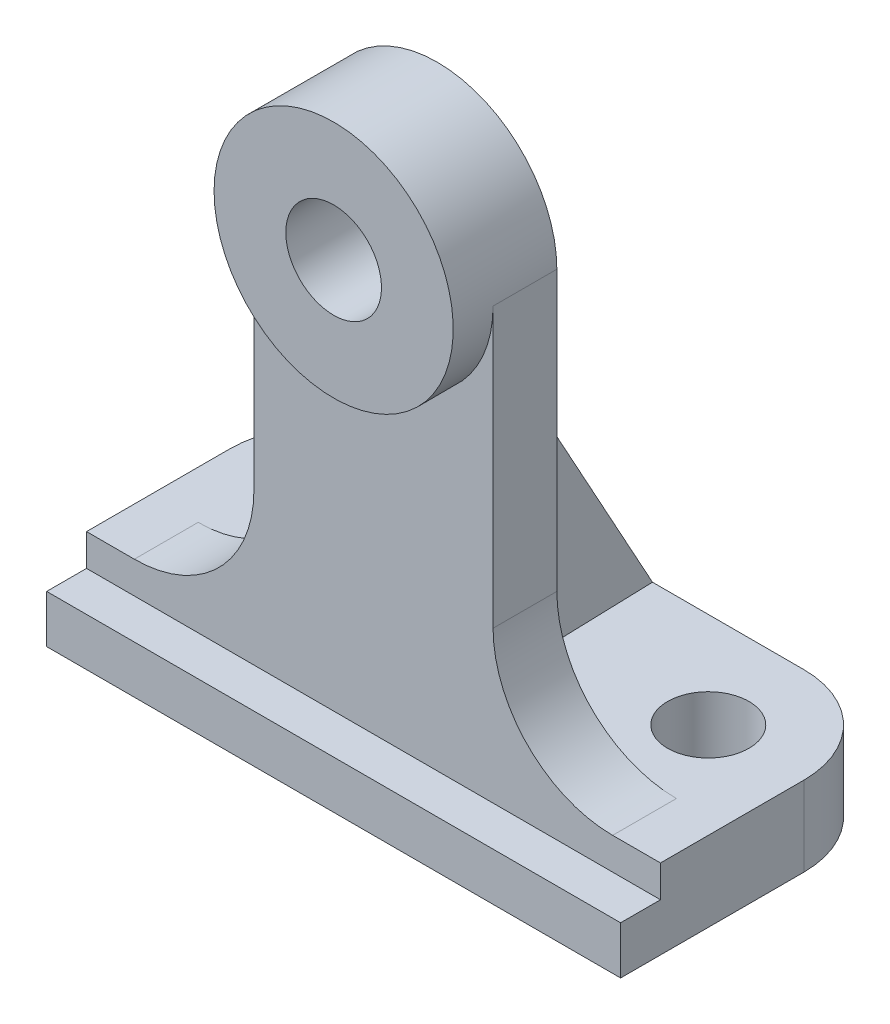
SolidWorks part; units mm, degrees
ref_plane "Front Plane" through (0, 0, 0) normal (0, 0, 1) x (1, 0, 0)
ref_plane "Top Plane" through (0, 0, 0) normal (0, 1, 0) x (1, 0, 0)
ref_plane "Right Plane" through (0, 0, 0) normal (1, 0, 0) x (0, 0, -1)
sketch "Sketch1" plane through (0, 0, 0) normal (0, 0, 1) x (1, 0, 0)
  line L1 (-36, 5) -> (36, 5)
  line L2 (-36, 5) -> (-36, -5)
  line L3 (-36, -5) -> (36, -5)
  line L4 (36, 5) -> (36, -5)
  line L5 (-36, 5) -> (36, -5) construction
  line L6 (-36, -5) -> (36, 5) construction
  point P0 (0, 0)
  dimension "D1" = 10
  dimension "D2" = 72
extrude "Boss-Extrude1" add sketch "Sketch1" along normal blind 35
sketch "Sketch2" plane through (0, 0, 35) normal (0, 0, 1) x (1, 0, 0)
  line L0 (-36, 5) -> (-36, 1)
  line L1 (-36, 5) -> (-36, -5) construction
  line L2 (-36, 1) -> (36, 1)
  line L3 (36, -5) -> (36, 5) construction
  line L4 (36, 1) -> (36, 5)
  line L5 (36, 5) -> (-36, 5)
  dimension "D1" = 4
extrude "Cut-Extrude1" cut sketch "Sketch2" against normal blind 5
sketch "Sketch3" plane through (0, 5, 0) normal (0, 1, 0) x (1, 0, 0)
  line L0 (-15, -30) -> (-15, -22)
  line L1 (36, -30) -> (-36, -30) construction
  line L2 (-15, -22) -> (15, -22)
  line L3 (15, -22) -> (15, -30)
  line L4 (15, -30) -> (-15, -30)
  dimension "D1" = 8
  dimension "D2" = 30
  dimension "D3" = 15
extrude "Boss-Extrude3" add sketch "Sketch3" along normal blind 50 contours L2 L3 L4 L0
sketch "Sketch5" plane through (0, 0, 22) normal (0, 0, -1) x (-1, 0, 0)
  line L0 (15, 55) -> (-15, 55) construction
  circle A0 centre (0, 55) radius 15
  circle A1 centre (0, 55) radius 6
  dimension "D1" = 30
  dimension "D2" = 12
extrude "Extrude-Thin1" add sketch "Sketch5" against normal blind 13 thin contours A0
sketch "Sketch6" plane through (0, 0, 30) normal (0, 0, 1) x (1, 0, 0)
  line L1 (6, 55) -> (-6, 55)
  line L2 (6, 55) -> (-6, 55)
  arc A1 (-6, 55) -> (6, 55) centre (0, 55) ccw
  arc A2 (-6, 55) -> (6, 55) centre (0, 55) ccw
  dimension "D1" = 0
extrude "Cut-Extrude2" cut sketch "Sketch6" against normal blind 13
fillet "Fillet2" radius 15 2 edges at (-15, 5, 26) (15, 5, 26)
sketch "Sketch7" plane through (0, 0, 0) normal (1, 0, 0) x (0, 0, -1)
  line L0 (0, 5) -> (-22, 45)
  line L1 (-22, 55) -> (-22, 20) construction
  dimension "D1" = 40
rib "Rib12" sketch "Sketch7" sketch "Sketch7" thickness 10 extrusion direction parallel to sketch draft on yes draft angle 2 parameters "D1"=10, "D3"=2
fillet "Fillet3" radius 12 2 edges at (-36, 0, 0) (36, 0, 0)
sketch "Sketch9" plane through (0, 0, 0) normal (0, 1, 0) x (1, 0, 0)
  circle A0 centre (-24, -12) radius 5.1
  circle A1 centre (24, -12) radius 5.1
  arc A2 (-24, 0) -> (-36, -12) centre (-24, -12) ccw construction
  arc A3 (36, -12) -> (24, 0) centre (24, -12) ccw construction
  dimension "D1" = 10.2
extrude "Cut-Extrude5" cut sketch "Sketch9" against normal mid plane 10
